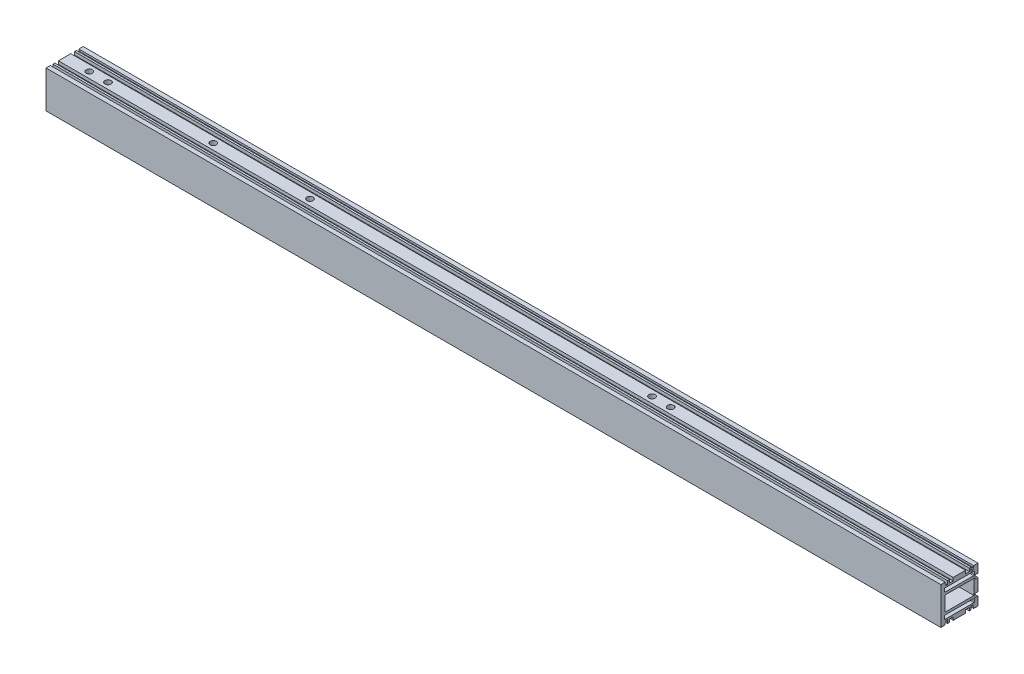
SolidWorks part; units mm, degrees
ref_plane "前视基准面" through (0, 0, 0) normal (0, 0, 1) x (1, 0, 0)
ref_plane "上视基准面" through (0, 0, 0) normal (0, 1, 0) x (1, 0, 0)
ref_plane "右视基准面" through (0, 0, 0) normal (1, 0, 0) x (0, 0, -1)
sketch "草图1" plane through (0, 0, 0) normal (1, 0, 0) x (0, 0, -1)
  line L0 (-15, 15) -> (15, -15) construction
  line L1 (-15, 15) -> (-11.5, 15)
  line L2 (-15, 15) -> (-15, -15)
  line L3 (-15, -15) -> (-11.5, -15)
  line L4 (15, 15) -> (15, 8)
  line L5 (15, 15) -> (-15, -15) construction
  line L6 (-11.5, 15) -> (-11.5, 13.5)
  line L7 (-11.5, 13.5) -> (-11, 13.5)
  line L8 (-11, 13.5) -> (-11, 12)
  line L9 (-11, 12) -> (-9.5, 12)
  line L10 (-9.5, 12) -> (-9.5, 15)
  line L11 (-9.5, 15) -> (-8, 15)
  line L12 (-8, 15) -> (-8, 12.5)
  line L13 (-8, 12.5) -> (-5, 12.5)
  line L14 (-5, 12.5) -> (-5, 15)
  line L15 (-5, 15) -> (5, 15)
  line L16 (0, 21.5201) -> (0, -18.309) construction
  line L17 (0, 55) -> (0, -55) construction
  line L18 (5, 12.5) -> (5, 15)
  line L19 (8, 12.5) -> (5, 12.5)
  line L20 (8, 15) -> (8, 12.5)
  line L21 (9.5, 15) -> (8, 15)
  line L22 (9.5, 12) -> (9.5, 15)
  line L23 (11, 12) -> (9.5, 12)
  line L24 (11, 13.5) -> (11, 12)
  line L25 (11.5, 13.5) -> (11, 13.5)
  line L26 (11.5, 15) -> (11.5, 13.5)
  line L27 (8, 15) -> (9.5, 15)
  line L28 (11.5, 15) -> (15, 15)
  line L29 (-19.8303, 0) -> (22.13, 0) construction
  line L30 (55, 0) -> (-55, 0) construction
  line L31 (8, -15) -> (9.5, -15)
  line L32 (11.5, -15) -> (11.5, -13.5)
  line L33 (11.5, -13.5) -> (11, -13.5)
  line L34 (11, -13.5) -> (11, -12)
  line L35 (11, -12) -> (9.5, -12)
  line L36 (9.5, -12) -> (9.5, -15)
  line L37 (9.5, -15) -> (8, -15)
  line L38 (8, -15) -> (8, -12.5)
  line L39 (8, -12.5) -> (5, -12.5)
  line L40 (5, -12.5) -> (5, -15)
  line L41 (-5, -15) -> (5, -15)
  line L42 (-5, -12.5) -> (-5, -15)
  line L43 (-8, -12.5) -> (-5, -12.5)
  line L44 (-8, -15) -> (-8, -12.5)
  line L45 (-9.5, -15) -> (-8, -15)
  line L46 (-9.5, -12) -> (-9.5, -15)
  line L47 (-11, -12) -> (-9.5, -12)
  line L48 (-11, -13.5) -> (-11, -12)
  line L49 (-11.5, -13.5) -> (-11, -13.5)
  line L50 (-11.5, -15) -> (-11.5, -13.5)
  line L51 (-9.5, -15) -> (-8, -15)
  line L52 (-5, -15) -> (5, -15)
  line L53 (8, -15) -> (9.5, -15)
  line L54 (11.5, -15) -> (15, -15)
  line L55 (15, 8) -> (12.5, 8)
  line L56 (12.5, 8) -> (12.5, 5)
  line L57 (12.5, 5) -> (15, 5)
  line L58 (12.5, -5) -> (15, -5)
  line L59 (12.5, -8) -> (12.5, -5)
  line L60 (15, -8) -> (12.5, -8)
  line L61 (15, 5) -> (15, -5)
  line L62 (15, -8) -> (15, -15)
  line L63 (12, -10.5) -> (12, -8.5)
  line L64 (-11.5, 11) -> (11.5, 11)
  line L65 (-12, 10.5) -> (-12, 8.5)
  line L66 (-11.5, 8) -> (11.5, 8)
  line L67 (12, 10.5) -> (12, 8.5)
  line L68 (-11.5, -8) -> (11.5, -8)
  line L69 (-12, -10.5) -> (-12, -8.5)
  line L70 (-11.5, -11) -> (11.5, -11)
  line L72 (-11.75, 6) -> (11.75, 6)
  line L73 (-11.75, 6) -> (-11.75, -6)
  line L74 (-11.75, -6) -> (11.75, -6)
  line L75 (11.75, 6) -> (11.75, -6)
  arc A0 (12, 8.5) -> (11.5, 8) centre (11.5, 8.5) cw
  arc A1 (11.5, 11) -> (12, 10.5) centre (11.5, 10.5) cw
  arc A2 (-11.5, 11) -> (-12, 10.5) centre (-11.5, 10.5) ccw
  arc A3 (-11.5, 8) -> (-12, 8.5) centre (-11.5, 8.5) cw
  arc A8 (-11.5, -8) -> (-12, -8.5) centre (-11.5, -8.5) ccw
  arc A9 (-11.5, -11) -> (-12, -10.5) centre (-11.5, -10.5) cw
  arc A10 (11.5, -11) -> (12, -10.5) centre (11.5, -10.5) ccw
  arc A11 (12, -8.5) -> (11.5, -8) centre (11.5, -8.5) ccw
  point P69 (12, 11)
  point P72 (-12, 11)
  point P77 (-11, -13.5)
  point P80 (11, -13.5)
  point P83 (11, 13.5)
  point P86 (-11, 13.5)
  point P99 (-12, -11)
  point P100 (12, -11)
  dimension "D17" = 0.5
  dimension "D1" = 3.5
  dimension "D2" = 1.5
  dimension "D3" = 0.5
  dimension "D4" = 1.5
  dimension "D5" = 3
  dimension "D6" = 30
  dimension "D7" = 30
  dimension "D8" = 1.5
  dimension "D9" = 2.5
  dimension "D10" = 3
  dimension "D11" = 2.5
  dimension "D12" = 7
  dimension "D13" = 3
  dimension "D14" = 4
  dimension "D15" = 3
  dimension "D16" = 24
  dimension "D19" = 23.5
  dimension "D20" = 12
extrude "凸台-拉伸1" add sketch "草图1" along normal mid plane 722
hole_wizard "M6 螺纹孔1" positions "草图3" profile "草图2" tap size "M6" standard "GB"
sketch "草图3" plane through (0, -15, 0) normal (0, -1, 0) x (-1, 0, 0)
  point P0 (-341, 0)
  point P3 (-326, 0)
  point P6 (-246, 0)
  point P9 (-231, 0)
  point P12 (-161, 0)
  point P15 (-146, 0)
  point P18 (326, 0)
  point P21 (341, 0)
sketch "草图2" plane through (341, -15, 0) normal (1, 0, 0) x (0, 0, -1)
  line L0 (0, 0) -> (0, 20.5022)
  line L1 (0, 20.5022) -> (2.5, 19)
  line L2 (2.5, 19) -> (2.5, 0)
  line L5 (2.5, 0) -> (0, 0)
  line L10 (0, 20.5022) -> (-2.5, 19) construction
  line L11 (0, -6.35) -> (0, 107.95) construction
  dimension "螺纹孔钻头直径" = 5
  dimension "螺纹孔钻头深度" = 19
  dimension "导头角度" = 118
cosmetic thread "孔螺蚊线1" parameters "D1"=9, "D2"=6
cosmetic thread "孔螺蚊线2" parameters "D1"=9, "D2"=6
cosmetic thread "孔螺蚊线3" parameters "D1"=9, "D2"=6
cosmetic thread "孔螺蚊线4" parameters "D1"=9, "D2"=6
cosmetic thread "孔螺蚊线5" parameters "D1"=9, "D2"=6
cosmetic thread "孔螺蚊线6" parameters "D1"=9, "D2"=6
cosmetic thread "孔螺蚊线7" parameters "D1"=9, "D2"=6
cosmetic thread "孔螺蚊线8" parameters "D1"=9, "D2"=6
hole_wizard "M6 螺纹孔2" positions "草图5" profile "草图4" tap size "M6" standard "GB"
sketch "草图5" plane through (0, 15, 0) normal (0, 1, 0) x (1, 0, 0)
  line L0 (361, 15) -> (-361, 15) construction
  line L1 (-361, 11.5) -> (-361, 15) construction
  point P0 (128, 0)
  point P3 (113, 0)
  point P6 (-341, 0)
  point P9 (-326, 0)
  point P12 (-241, 0)
  point P14 (-163, 0)
  dimension "D1" = 15
  dimension "D2" = 15
  dimension "D3" = 120
  dimension "D4" = 198
sketch "草图4" plane through (128, 15, 0) normal (1, 0, 0) x (0, 0, 1)
  line L0 (0, 0) -> (0, 20.5022)
  line L1 (0, 20.5022) -> (2.5, 19)
  line L2 (2.5, 19) -> (2.5, 0)
  line L5 (2.5, 0) -> (0, 0)
  line L10 (0, 20.5022) -> (-2.5, 19) construction
  line L11 (0, -6.35) -> (0, 107.95) construction
  dimension "螺纹孔钻头直径" = 5
  dimension "螺纹孔钻头深度" = 19
  dimension "导头角度" = 118
cosmetic thread "孔螺蚊线9" parameters "D1"=9, "D2"=6
cosmetic thread "孔螺蚊线10" parameters "D1"=9, "D2"=6
cosmetic thread "孔螺蚊线11" parameters "D1"=9, "D2"=6
cosmetic thread "孔螺蚊线12" parameters "D1"=9, "D2"=6
cosmetic thread "孔螺蚊线15" parameters "D1"=9, "D2"=6
cosmetic thread "孔螺蚊线16" parameters "D1"=9, "D2"=6
hole_wizard "M6 螺纹孔3" positions "草图7" profile "草图6" tap size "M6" standard "GB"
sketch "草图7" plane through (0, 0, -15) normal (0, 0, -1) x (-1, 0, 0)
  line L0 (-361, -15) -> (361, -15) construction
  line L1 (-361, -8) -> (-361, -15) construction
  point P0 (-326, 0)
  point P2 (-341, 0)
  dimension "D1" = 15
  dimension "D2" = 15
  dimension "D3" = 20
  dimension "D4" = 35
sketch "草图6" plane through (326, 0, -15) normal (1, 0, 0) x (0, 1, 0)
  line L0 (0, 0) -> (0, 20.5022)
  line L1 (0, 20.5022) -> (2.5, 19)
  line L2 (2.5, 19) -> (2.5, 0)
  line L5 (2.5, 0) -> (0, 0)
  line L10 (0, 20.5022) -> (-2.5, 19) construction
  line L11 (0, -6.35) -> (0, 107.95) construction
  dimension "螺纹孔钻头直径" = 5
  dimension "螺纹孔钻头深度" = 19
  dimension "导头角度" = 118
cosmetic thread "孔螺蚊线13" parameters "D1"=3.25, "D2"=6
cosmetic thread "孔螺蚊线14" parameters "D1"=3.25, "D2"=6
